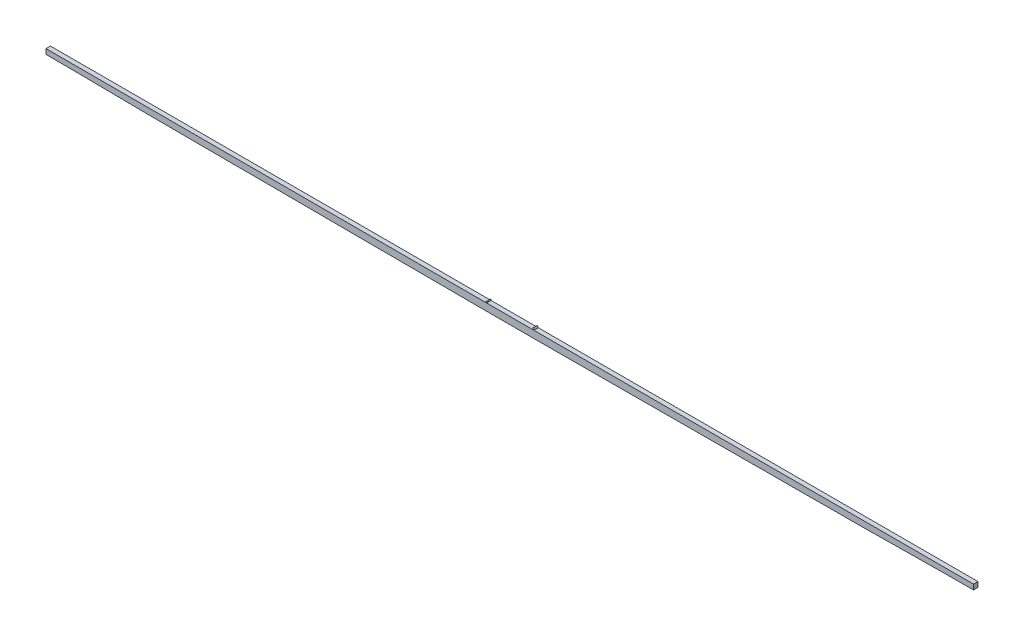
SolidWorks part; units mm, degrees
ref_plane "前视基准面" through (0, 0, 0) normal (0, 0, 1) x (1, 0, 0)
ref_plane "上视基准面" through (0, 0, 0) normal (0, 1, 0) x (1, 0, 0)
ref_plane "右视基准面" through (0, 0, 0) normal (1, 0, 0) x (0, 0, -1)
sketch "Model" plane through (0, 0, 0) normal (0, 0, 1) x (1, 0, 0)
  line L0 (143.7549, 180.0616) -> (637.7669, 180.0616)
  line L1 (142.7584, 171.9978) -> (221.5172, 172.2628)
  line L2 (221.5172, 172.2628) -> (223.5172, 172.2628)
  line L3 (223.5172, 172.2628) -> (311.5172, 172.5727)
  line L4 (311.5172, 172.5727) -> (313.5172, 172.5727)
  line L5 (313.5172, 172.5727) -> (411.7672, 172.9426)
  line L6 (411.7672, 172.9426) -> (413.7672, 172.9426)
  line L7 (413.7672, 172.9426) -> (429.7672, 172.934)
  line L8 (429.7672, 172.934) -> (431.7672, 172.934)
  line L9 (431.7672, 172.934) -> (520.7532, 173.3198)
  line L10 (520.7532, 173.3198) -> (522.7532, 173.3284)
  line L11 (522.7532, 173.3284) -> (605.4176, 174.2668)
  line L12 (605.4176, 174.2668) -> (607.4176, 174.2668)
  line L13 (635.7669, 174.3895) -> (637.7669, 174.3895)
  line L14 (142.7627, 180.0616) -> (116.7627, 180.0616)
  line L15 (142.7584, 171.9978) -> (116.7627, 171.9978)
  line L16 (142.7627, 180.0616) -> (142.7627, 181.8815)
  line L17 (142.7627, 181.8815) -> (143.7549, 180.0616)
  line L18 (607.4176, 174.2668) -> (635.7669, 174.3895)
  line L19 (637.7669, 180.0616) -> (637.7669, 174.3895)
  line L20 (89.7706, 180.0616) -> (-404.2414, 180.0616)
  line L21 (90.7671, 171.9978) -> (12.0082, 172.2628)
  line L22 (12.0082, 172.2628) -> (10.0082, 172.2628)
  line L23 (10.0082, 172.2628) -> (-77.9918, 172.5727)
  line L24 (-77.9918, 172.5727) -> (-79.9918, 172.5727)
  line L25 (-79.9918, 172.5727) -> (-178.2417, 172.9426)
  line L26 (-178.2417, 172.9426) -> (-180.2417, 172.9426)
  line L27 (-180.2417, 172.9426) -> (-196.2417, 172.934)
  line L28 (-196.2417, 172.934) -> (-198.2417, 172.934)
  line L29 (-198.2417, 172.934) -> (-287.2277, 173.3198)
  line L30 (-287.2277, 173.3198) -> (-289.2277, 173.3284)
  line L31 (-289.2277, 173.3284) -> (-371.8921, 174.2668)
  line L32 (-371.8921, 174.2668) -> (-373.8921, 174.2668)
  line L33 (-402.2414, 174.3895) -> (-404.2414, 174.3895)
  line L34 (90.7627, 180.0616) -> (116.7627, 180.0616)
  line L35 (90.7671, 171.9978) -> (116.7627, 171.9978)
  line L36 (90.7627, 180.0616) -> (90.7627, 181.8815)
  line L37 (90.7627, 181.8815) -> (89.7706, 180.0616)
  line L38 (-373.8921, 174.2668) -> (-402.2414, 174.3895)
  line L39 (-404.2414, 180.0616) -> (-404.2414, 174.3895)
extrude "凸台-拉伸3" add sketch "Model" along normal blind 5
